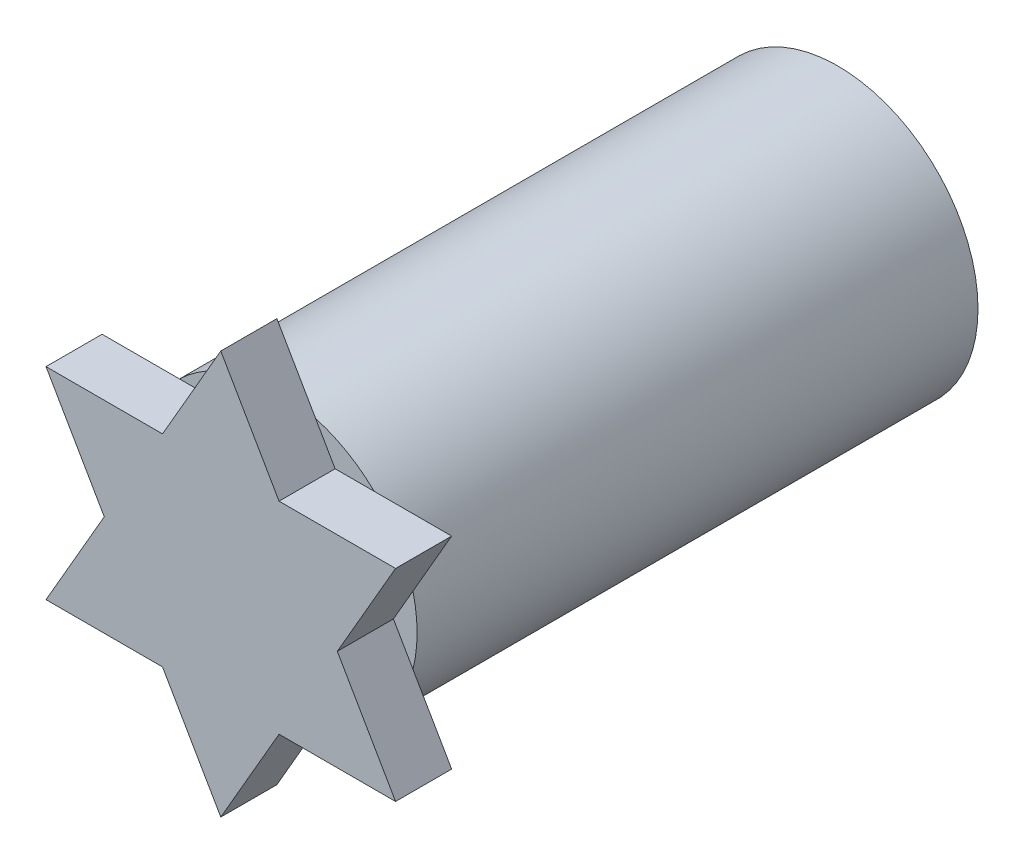
SolidWorks part; units mm, degrees
ref_plane "정면" through (0, 0, 0) normal (0, 0, 1) x (1, 0, 0)
ref_plane "윗면" through (0, 0, 0) normal (0, 1, 0) x (1, 0, 0)
ref_plane "우측면" through (0, 0, 0) normal (1, 0, 0) x (0, 0, -1)
sketch "스케치1" plane through (0, 0, 0) normal (0, 0, 1) x (1, 0, 0)
  circle A0 centre (0, 0) radius 2.5
  dimension "D1" = 5
extrude "보스-돌출1" add sketch "스케치1" along normal blind 10
sketch "스케치2" plane through (0, 0, 10) normal (0, 0, 1) x (1, 0, 0)
  line L1 (3.1161, 1.7991) -> (-3.1161, 1.7991)
  line L2 (-3.1161, 1.7991) -> (0, -3.5982)
  line L3 (0, -3.5982) -> (3.1161, 1.7991)
  line L4 (0, 3.5982) -> (-3.1161, -1.7991)
  line L5 (-3.1161, -1.7991) -> (3.1161, -1.7991)
  line L6 (3.1161, -1.7991) -> (0, 3.5982)
  circle A0 centre (0, 0) radius 1.7991 construction
  circle A1 centre (0, 0) radius 1.7991 construction
  point P1 (0, 0)
  point P11 (0, 0)
  circle M3 centre (0, 0) radius 2.5
  dimension "D1" = 3.5982
extrude "보스-돌출2" add sketch "스케치2" along normal blind 1 contours L1 L2 M3 | L4 L1 L2 M3 | L1 L6 L4 M3 | L3 L1 M3 | L6 L3 L1 M3 | L5 L6 M3 | L6 L3 L5 M3 | L2 L3 M3 | L5 L2 L3 M3 | L5 L2 L4 M3 | L4 L5 M3 | L3 L6 L1 L4 L2 L5 | L6 L4 M3
